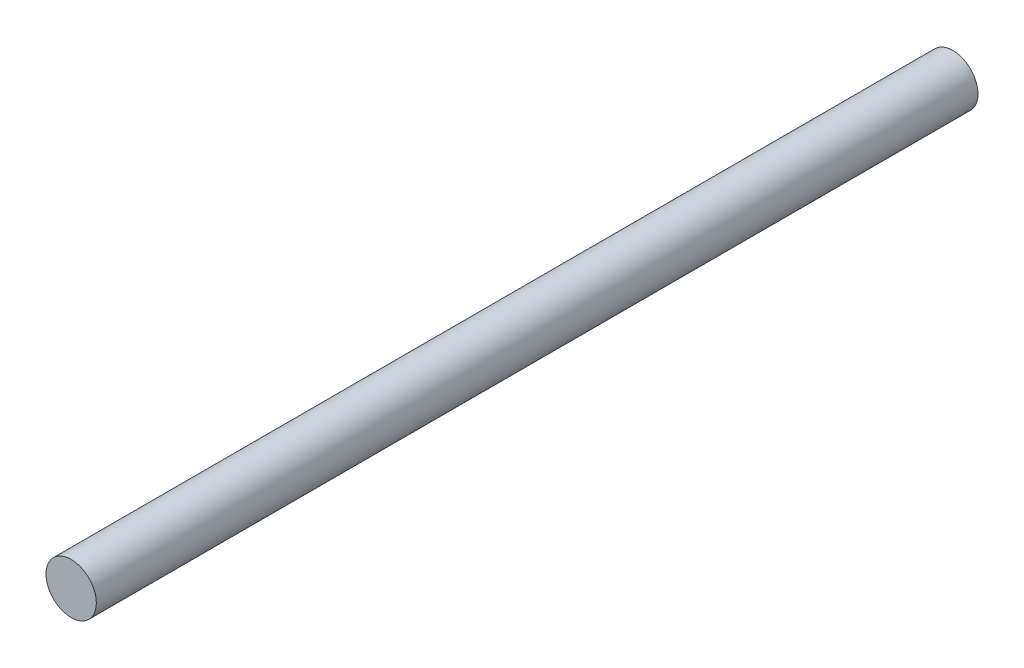
SolidWorks part; units mm, degrees
ref_plane "Front Plane" through (0, 0, 0) normal (0, 0, 1) x (1, 0, 0)
ref_plane "Top Plane" through (0, 0, 0) normal (0, 1, 0) x (1, 0, 0)
ref_plane "Right Plane" through (0, 0, 0) normal (1, 0, 0) x (0, 0, -1)
sketch "Sketch1" plane through (0, 0, 0) normal (0, 0, 1) x (1, 0, 0)
  circle A0 centre (0, 0) radius 2
  dimension "D1" = 4
extrude "Boss-Extrude1" add sketch "Sketch1" along normal blind 70
